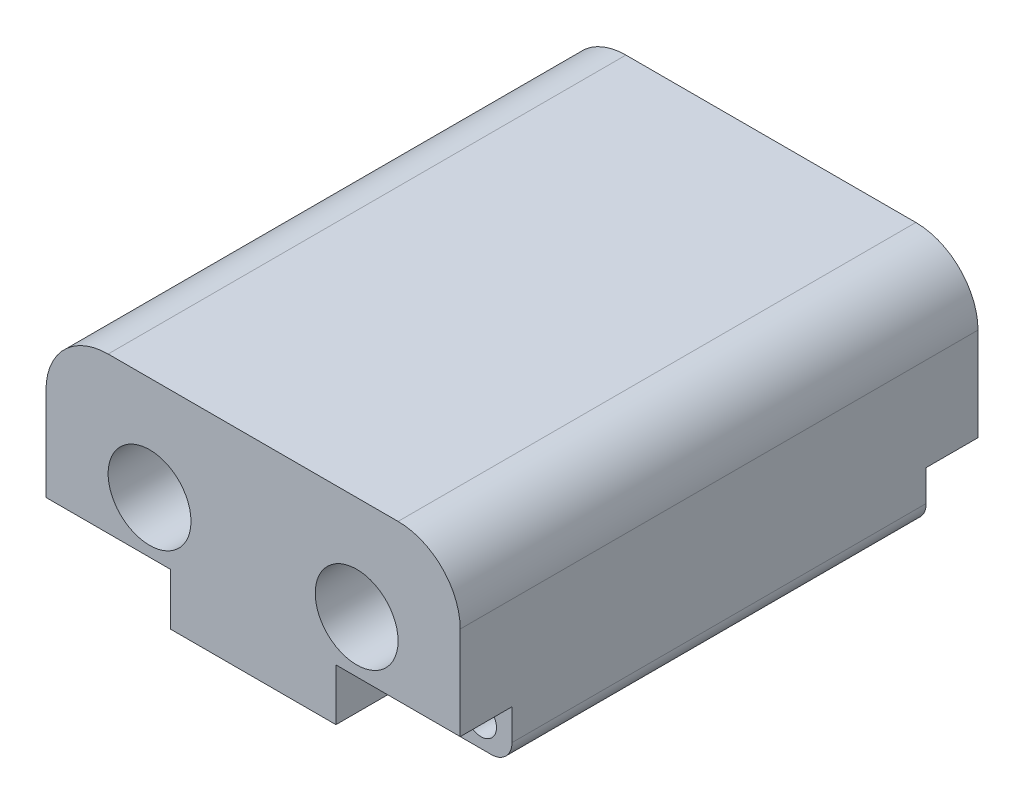
SolidWorks part; units mm, degrees
ref_plane "Plan de face" through (0, 0, 0) normal (0, 0, 1) x (1, 0, 0)
ref_plane "Plan de dessus" through (0, 0, 0) normal (0, 1, 0) x (1, 0, 0)
ref_plane "Plan de droite" through (0, 0, 0) normal (1, 0, 0) x (0, 0, -1)
sketch "Esquisse1" plane through (0, 0, 0) normal (0, 0, 1) x (1, 0, 0)
  line L1 (-20, -10) -> (-20, 10)
  line L2 (-20, 10) -> (20, 10)
  line L3 (20, 10) -> (20, -10)
  line L6 (-24.655, 0) -> (32.2805, 0) construction
  line L7 (-20, -10) -> (20, -10)
  circle A2 centre (-10, 0) radius 4
  circle A3 centre (10, 0) radius 4
  point P1 (0, 10)
  point P12 (20, 0)
  point P14 (-20, 0)
  dimension "D1" = 8
  dimension "D2" = 8
  dimension "D3" = 10
  dimension "D5" = 10
  dimension "D6" = 20
  dimension "D4" = 10
  dimension "D7" = 40
extrude "Boss.-Extru.1" add sketch "Esquisse1" along normal blind 50
sketch "Esquisse2" plane through (0, 0, 50) normal (0, 0, 1) x (1, 0, 0)
  line L0 (0, 13.0325) -> (0, -12.867) construction
  line L1 (-20, -10) -> (-8, -10)
  line L2 (-20, -10) -> (-20, -5)
  line L3 (-20, -5) -> (-8, -5)
  line L4 (-8, -10) -> (-8, -5)
  line L5 (20, -5) -> (8, -5)
  line L6 (8, -10) -> (8, -5)
  line L7 (20, -10) -> (8, -10)
  line L8 (20, -10) -> (20, -5)
  dimension "D1" = 12
  dimension "D2" = 5
extrude "Enlèv. mat.-Extru.1" cut sketch "Esquisse2" against normal blind 5
sketch "Esquisse3" plane through (0, 0, 45) normal (0, 0, 1) x (1, 0, 0)
  line L0 (-8, -5) -> (-20, -5) construction
  line L1 (-14, -5) -> (-14, -14.2737) construction
  line L2 (0, 11.3362) -> (0, -13.3221) construction
  line L3 (-20, -5) -> (-20, -10) construction
  circle A0 centre (-17, -7.5) radius 1.5
  circle A2 centre (-11, -7.5) radius 1.5
  circle A3 centre (17, -7.5) radius 1.5
  circle A4 centre (11, -7.5) radius 1.5
  dimension "D1" = 2.5
  dimension "D2" = 3
  dimension "D3" = 3
extrude "Enlèv. mat.-Extru.2" cut sketch "Esquisse3" against normal blind 8
ref_plane "Plan1" through (0, 0, 25) normal (0, 0, 1) x (1, 0, 0)
mirror "Symétrie1" about plane through (0, 0, 25) normal (0, 0, 1) of "Enlèv. mat.-Extru.2", "Enlèv. mat.-Extru.1"
fillet "Congé2" radius 6 2 edges at (20, 10, 25) (-20, 10, 25)
fillet "Congé3" radius 2 2 edges at (-20, -10, 25) (20, -10, 25)
